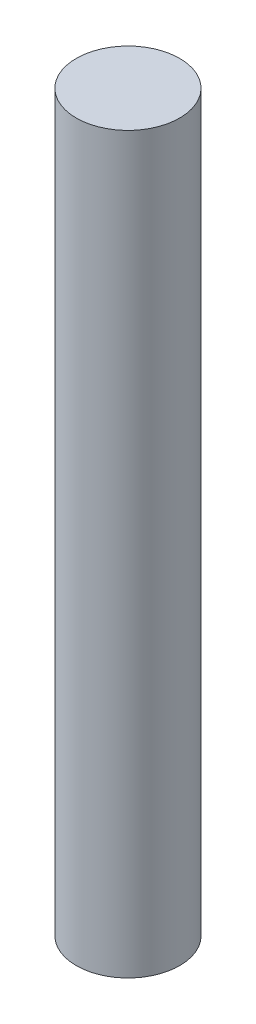
SolidWorks part; units mm, degrees
ref_plane "Plan de face" through (0, 0, 0) normal (0, 0, 1) x (1, 0, 0)
ref_plane "Plan de dessus" through (0, 0, 0) normal (0, 1, 0) x (1, 0, 0)
ref_plane "Plan de droite" through (0, 0, 0) normal (1, 0, 0) x (0, 0, -1)
sketch "Esquisse1" plane through (0, 0, 0) normal (0, 1, 0) x (1, 0, 0)
  circle A0 centre (0, 0) radius 5
  dimension "D1" = 10
extrude "Boss.-Extru.1" add sketch "Esquisse1" against normal blind 71
